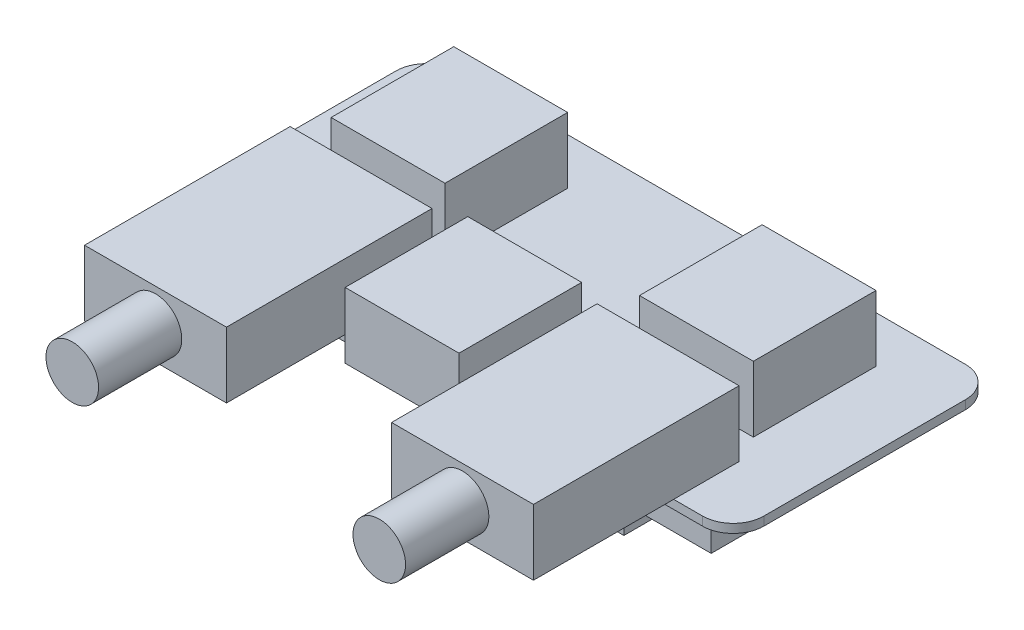
SolidWorks part; units mm, degrees
ref_plane "Front Plane" through (0, 0, 0) normal (0, 0, 1) x (1, 0, 0)
ref_plane "Top Plane" through (0, 0, 0) normal (0, 1, 0) x (1, 0, 0)
ref_plane "Right Plane" through (0, 0, 0) normal (1, 0, 0) x (0, 0, -1)
sketch "Sketch1" plane through (0, 0, 0) normal (0, 1, 0) x (1, 0, 0)
  line L1 (-29, 30) -> (29, 30)
  line L2 (-32.5, 26.5) -> (-32.5, 3.5)
  line L3 (-29, 0) -> (29, 0)
  line L4 (32.5, 26.5) -> (32.5, 3.5)
  line L5 (-29, 26.5) -> (29, 26.5)
  line L6 (-29, 26.5) -> (-29, 3.5)
  line L7 (-29, 3.5) -> (29, 3.5)
  line L8 (29, 26.5) -> (29, 3.5)
  line L16 (-36.57, 16.9) -> (-33.9814, 16.9)
  line L17 (8.9, -0.8996) -> (8.9, -2.1824)
  line L18 (21.5, -0.8996) -> (21.5, -2.1824)
  arc A0 (-29, 30) -> (-32.5, 26.5) centre (-29, 26.5) ccw
  arc A5 (-29, 0) -> (-32.5, 3.5) centre (-29, 3.5) cw
  arc A6 (29, 0) -> (32.5, 3.5) centre (29, 3.5) ccw
  arc A7 (32.5, 26.5) -> (29, 30) centre (29, 26.5) ccw
  dimension "D15" = 3.5
  dimension "D1" = 30
  dimension "D2" = 23
  dimension "D4" = 3.5
  dimension "D12" = 16.9
  dimension "D13" = 41.4
  dimension "D14" = 54
extrude "Boss-Extrude1" add sketch "Sketch1" along normal blind 1 contours L3 A6 L4 A7 L1 A0 L2 A5
sketch "Sketch2" plane through (0, 0, 0) normal (0, -1, 0) x (1, 0, 0)
  line L1 (-25.8116, -5.3) -> (-11.8116, -5.3)
  line L2 (-25.8116, -5.3) -> (-25.8116, -18.3)
  line L3 (-25.8116, -18.3) -> (-11.8116, -18.3)
  line L4 (-11.8116, -5.3) -> (-11.8116, -18.3)
  line L5 (-29, 0) -> (29, 0) construction
  dimension "D1" = 14
  dimension "D2" = 13
  dimension "D3" = 5.3
extrude "Boss-Extrude2" add sketch "Sketch2" along normal blind 7.5
sketch "Sketch3" plane through (0, 0, 0) normal (0, -1, 0) x (1, 0, 0)
  line L0 (-1.8116, -17.4903) -> (-16.8116, -17.4903)
  line L1 (-1.8116, -1.7954) -> (28.1884, -1.7954)
  line L2 (-1.8116, -1.7954) -> (-1.8116, -21.7954)
  line L3 (-1.8116, -21.7954) -> (28.1884, -21.7954)
  line L4 (28.1884, -1.7954) -> (28.1884, -21.7954)
  line L5 (-1.8116, -17.4903) -> (-1.8116, -6.1005)
  line L6 (-16.8116, -17.4903) -> (-16.8116, -6.1005)
  line L7 (-1.8116, -6.1005) -> (-16.8116, -6.1005)
  line L8 (-11.8116, -18.3) -> (-11.8116, -5.3) construction
  point P5 (-9.9147, -11.7954)
  line M17 (-11.8116, -5.3) -> (-11.8116, -18.3)
  dimension "D1" = 30
  dimension "D2" = 20
  dimension "D3" = 45
  dimension "D4" = 10
extrude "Boss-Extrude3" add sketch "Sketch3" along normal blind 4 contours L4 L1 L2 L3 | L2 L7 L0 M17
sketch "Sketch5" plane through (0, -4, 0) normal (0, -1, 0) x (1, 0, 0)
  line L1 (-0.0754, -2.5871) -> (17.4349, -2.5871)
  line L2 (-0.0754, -2.5871) -> (-0.0754, -20.1599)
  line L3 (-0.0754, -20.1599) -> (17.4349, -20.1599)
  line L4 (17.4349, -2.5871) -> (17.4349, -20.1599)
extrude "Boss-Extrude4" add sketch "Sketch5" along normal blind 4
sketch "Sketch6" plane through (0, 1, 0) normal (0, 1, 0) x (1, 0, 0)
  line L0 (6.5, 8.7) -> (6.5, -5.3)
  line L1 (6.5, 8.7) -> (-6.5, 8.7)
  line L2 (-6.5, 8.7) -> (-6.5, -5.3)
  line L3 (6.5, -5.3) -> (-6.5, -5.3)
  line L4 (-29, 30) -> (29, 30) construction
  line L5 (-11.1, 24.7) -> (-24.1, 24.7)
  line L6 (-11.1, 24.7) -> (-11.1, 10.7)
  line L7 (-24.1, 24.7) -> (-24.1, 10.7)
  line L8 (-11.1, 10.7) -> (-24.1, 10.7)
  line L9 (24.1, 10.7) -> (11.1, 10.7)
  line L10 (11.1, 24.7) -> (11.1, 10.7)
  line L11 (24.1, 24.7) -> (11.1, 24.7)
  line L12 (24.1, 24.7) -> (24.1, 10.7)
  line L14 (-32.5, 26.5) -> (-32.5, 3.5) construction
  line L15 (32.5, 26.5) -> (32.5, 3.5) construction
  line L16 (-29, 0) -> (29, 0) construction
  dimension "D2" = 5.3
  dimension "D3" = 8.4
  dimension "D4" = 13
  dimension "D5" = 14
  dimension "D6" = 13
  dimension "D7" = 14
  dimension "D8" = 14
  dimension "D9" = 13
  dimension "D10" = 5.3
  dimension "D11" = 8.4
  dimension "D12" = 5.3
extrude "Boss-Extrude5" add sketch "Sketch6" along normal blind 7.5
sketch "Sketch7" plane through (0, 1, 0) normal (0, 1, 0) x (1, 0, 0)
  line L0 (-29, 0) -> (-6.5, 0) construction
  line L1 (-25.5447, 7.4637) -> (-9.3447, 7.4637)
  line L2 (-25.5447, 7.4637) -> (-25.5447, -16)
  line L3 (-25.5447, -16) -> (-9.3447, -16)
  line L4 (-9.3447, 7.4637) -> (-9.3447, -16)
  line L5 (9.5, 7.4637) -> (25.7, 7.4637)
  line L6 (25.7, 7.4637) -> (25.7, -16)
  line L7 (9.5, -16) -> (25.7, -16)
  line L8 (9.5, 7.4637) -> (9.5, -16)
  dimension "D1" = 16.2
  dimension "D2" = 16
  dimension "D3" = 16.2
extrude "Boss-Extrude6" add sketch "Sketch7" along normal blind 7.5
sketch "Sketch8" plane through (0, 0, 16) normal (0, 0, 1) x (1, 0, 0)
  circle A0 centre (-17.4447, 4.75) radius 3
  circle A1 centre (17.6, 4.75) radius 3
extrude "Boss-Extrude7" add sketch "Sketch8" along normal blind 9.5
